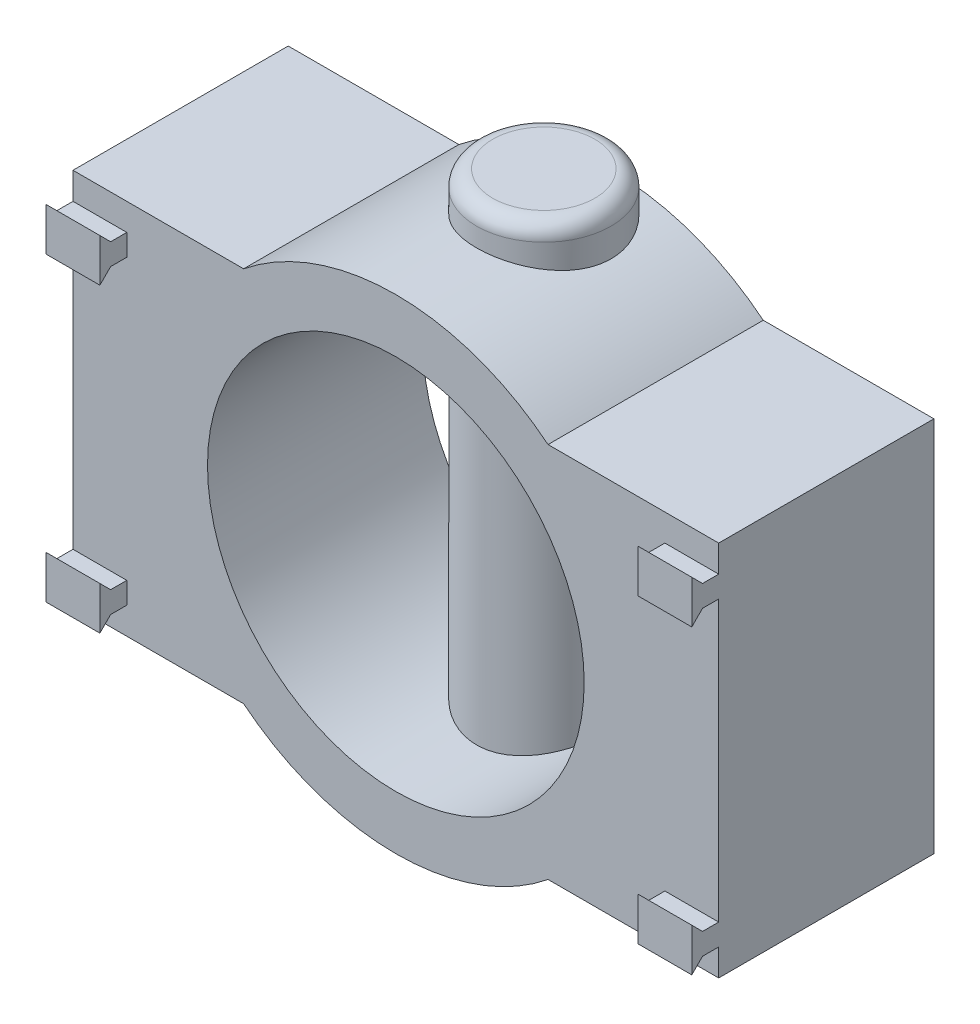
SolidWorks part; units mm, degrees
ref_plane "Plan de face" through (0, 0, 0) normal (0, 0, 1) x (1, 0, 0)
ref_plane "Plan de dessus" through (0, 0, 0) normal (0, 1, 0) x (1, 0, 0)
ref_plane "Plan de droite" through (0, 0, 0) normal (1, 0, 0) x (0, 0, -1)
sketch "Esquisse1" plane through (0, 0, 0) normal (0, 1, 0) x (1, 0, 0)
  circle A0 centre (0, 0) radius 12.5
  dimension "D1" = 25
extrude "Boss.-Extru.1" add sketch "Esquisse1" along normal blind 100
fillet "Congé1" radius 3 1 edges at (0, 100, 12.5)
sketch "Esquisse2" plane through (0, 0, 0) normal (0, -1, 0) x (1, 0, 0)
  circle A0 centre (0, 0) radius 3
  dimension "D1" = 6
extrude "Boss.-Extru.2" add sketch "Esquisse2" along normal blind 8
sketch "Esquisse3" plane through (0, -8, 0) normal (0, -1, 0) x (1, 0, 0)
  line L1 (-3, 3) -> (3, 3)
  line L2 (-3, 3) -> (-3, 1.8)
  line L3 (-3, 1.8) -> (3, 1.8)
  line L4 (3, 3) -> (3, 1.8)
  circle A0 centre (0, 0) radius 3 construction
  dimension "D1" = 1.2
extrude "Enlèv. mat.-Extru.1" cut sketch "Esquisse3" against normal up to surface (8 mm away) up to face at (0, 0, -3)
ref_plane "Plan1" through (0, 0, 12.5) normal (0, 0, 1) x (1, 0, 0)
sketch "Esquisse4" plane through (0, 0, 12.5) normal (0, 0, 1) x (1, 0, 0)
  line L0 (0, 0) -> (0, 97) construction
  line L1 (-12.5, 97) -> (12.5, 97) construction
  circle A0 centre (0, 48.5) radius 45
  circle A1 centre (0, 48.5) radius 35
  point P8 (0, 48.5)
  dimension "D1" = 90
  dimension "D2" = 10
extrude "Boss.-Extru.3" add sketch "Esquisse4" along normal blind 15 and the other way blind 25 separate body
ref_plane "Plan2" through (60, 0, 0) normal (1, 0, 0) x (0, 0, -1)
sketch "Esquisse5" plane through (60, 0, 0) normal (1, 0, 0) x (0, 0, -1)
  line L0 (-27.5, 93.5) -> (-27.5, 3.5) construction
  line L1 (-27.5, 83.5) -> (12.5, 83.5)
  line L2 (-27.5, 83.5) -> (-27.5, 13.5)
  line L3 (-27.5, 13.5) -> (12.5, 13.5)
  line L4 (12.5, 83.5) -> (12.5, 13.5)
  line L5 (12.5, 3.5) -> (12.5, 93.5) construction
extrude "Boss.-Extru.4" add sketch "Esquisse5" against normal up to surface (31.7157 mm away)
mirror "Symétrie1" about plane through (0, 0, 0) normal (1, 0, 0) of "Boss.-Extru.4"
sketch "Esquisse7" plane through (-60, 0, 0) normal (-1, 0, 0) x (0, 0, 1)
  line L0 (27.5, 78.5) -> (30.5, 78.5)
  line L1 (27.5, 83.5) -> (27.5, 13.5) construction
  line L2 (30.5, 78.5) -> (32.5, 80.5)
  line L3 (32.5, 80.5) -> (32.5, 72.5)
  line L4 (32.5, 72.5) -> (30.5, 74.5)
  line L5 (30.5, 74.5) -> (27.5, 74.5)
  line L6 (27.5, 74.5) -> (27.5, 78.5)
  line L7 (-34.3213, 48.5) -> (49.1987, 48.5) construction
  line L8 (-12.5, 13.5) -> (-12.5, 83.5) construction
  line L9 (27.5, 22.5) -> (27.5, 18.5)
  line L10 (30.5, 22.5) -> (27.5, 22.5)
  line L11 (32.5, 24.5) -> (30.5, 22.5)
  line L12 (32.5, 16.5) -> (32.5, 24.5)
  line L13 (30.5, 18.5) -> (32.5, 16.5)
  line L14 (27.5, 18.5) -> (30.5, 18.5)
  point P12 (-12.5, 48.5)
  line M8 (27.5, 13.5) -> (27.5, 83.5)
  dimension "D1" = 3
  dimension "D2" = 45
  dimension "D3" = 4
  dimension "D4" = 45
  dimension "D5" = 5
  dimension "D6" = 26
extrude "Boss.-Extru.5" add sketch "Esquisse7" against normal blind 10 contours L14 L13 L12 L11 L10 M8 | L3 L4 L5 L6 L0 L2
mirror "Symétrie2" about plane through (0, 0, 0) normal (1, 0, 0) of "Boss.-Extru.5"
ref_plane "Plan3" through (0, 0, -12.5) normal (0, 0, -1) x (-1, 0, 0)
sketch "Esquisse8" plane through (0, 0, -12.5) normal (0, 0, -1) x (-1, 0, 0)
  line L0 (-85.8836, 48.5) -> (92.2247, 48.5) construction
  line L1 (60, 13.5) -> (60, 83.5) construction
  circle A0 centre (0, 48.5) radius 3
  point P7 (60, 48.5)
  dimension "D1" = 6
extrude "Boss.-Extru.6" add sketch "Esquisse8" along normal blind 10 and the other way up to surface other way up to face at (0, 97, 12.5)
sketch "Esquisse9" plane through (0, 0, -22.5) normal (0, 0, -1) x (-1, 0, 0)
  line L1 (-3, 51.5) -> (3, 51.5)
  line L2 (-3, 51.5) -> (-3, 50.3)
  line L3 (-3, 50.3) -> (3, 50.3)
  line L4 (3, 51.5) -> (3, 50.3)
  circle A0 centre (0, 48.5) radius 3 construction
  dimension "D1" = 1.2
extrude "Enlèv. mat.-Extru.2" cut sketch "Esquisse9" against normal up to surface (10.3653 mm away)
